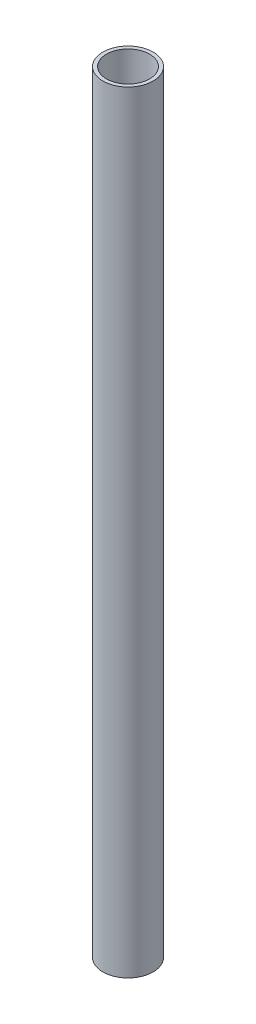
SolidWorks part; units mm, degrees
material "Laiton de décolletage, UNS C36000"
ref_plane "Plan de face" through (0, 0, 0) normal (0, 0, 1) x (1, 0, 0)
ref_plane "Plan de dessus" through (0, 0, 0) normal (0, 1, 0) x (1, 0, 0)
ref_plane "Plan de droite" through (0, 0, 0) normal (1, 0, 0) x (0, 0, -1)
sketch "Esquisse1" plane through (0, 0, 0) normal (0, 0, 1) x (1, 0, 0)
  line L0 (0, 107.5) -> (0, -107.5)
  point P4 (0, 0)
  dimension "D1" = 215
other "Tube rond 14X1(1)"
ref_plane "Plan1" through (0, 107.5, 0) normal (0, -1, 0) x (1, 0, 0)
sketch "tube rond" plane through (0, 107.5, 0) normal (0, -1, 0) x (1, 0, 0)
  line L0 (-7, 0) -> (7, 0) construction
  circle A0 centre (0, 0) radius 7
  circle A1 centre (0, 0) radius 6
  point P6 (0, 0)
  dimension "d" = 14
  dimension "e" = 1
